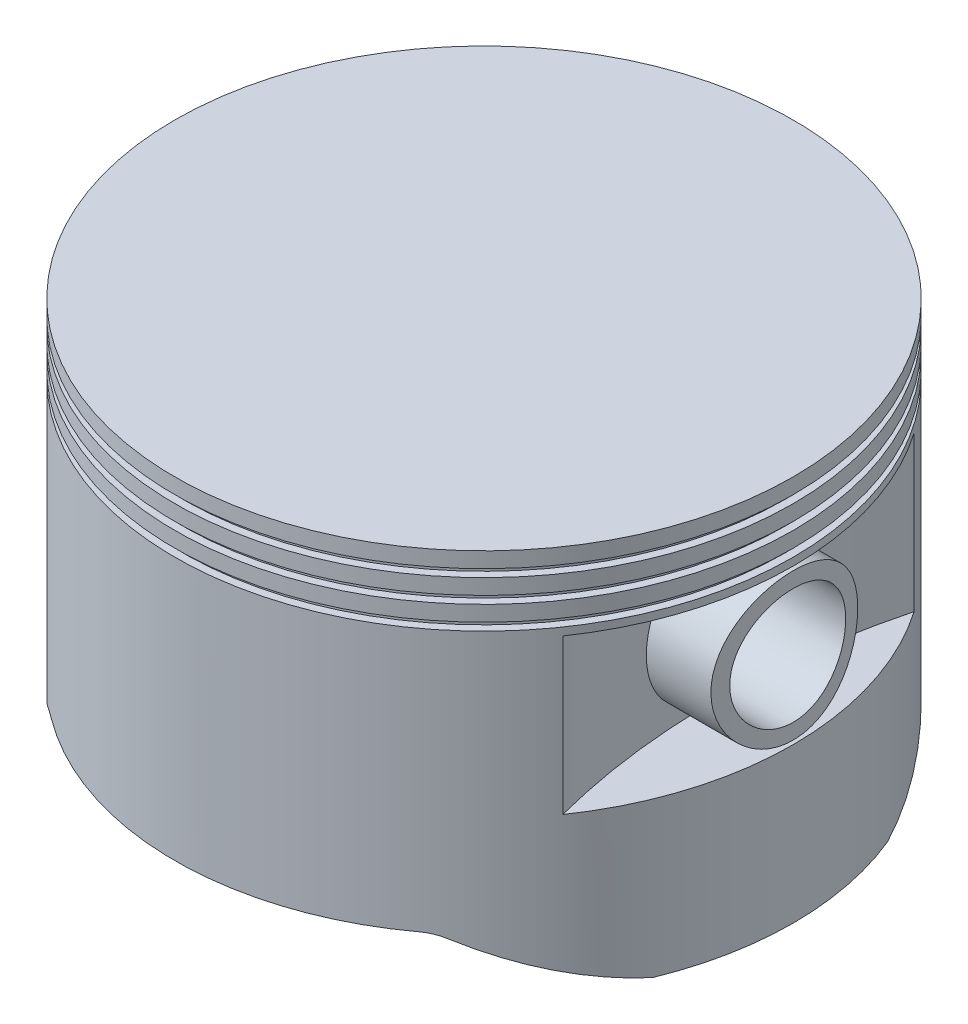
SolidWorks part; units mm, degrees
material "___"
ref_plane "Front Plane" through (0, 0, 0) normal (0, 0, 1) x (1, 0, 0)
ref_plane "Top Plane" through (0, 0, 0) normal (0, 1, 0) x (1, 0, 0)
ref_plane "Right Plane" through (0, 0, 0) normal (1, 0, 0) x (0, 0, -1)
sketch "Sketch1" plane through (0, 0, 0) normal (0, 0, 1) x (1, 0, 0)
  line L1 (0, 25) -> (-40, 25)
  line L2 (0, 25) -> (0, -25)
  line L3 (0, -25) -> (-40, -25)
  line L4 (-40, 25) -> (-40, -25)
  point P4 (-40, 11.1334)
  point P6 (0, 0)
  dimension "D1" = 50
  dimension "D2" = 40
revolve "Revolve1" add sketch "Sketch1" angle 360 about L2
sketch "Sketch2" plane through (0, 0, 0) normal (0, 0, 1) x (1, 0, 0)
  line L0 (-37, -25) -> (-25.8038, -18.5359)
  line L1 (-40, -25) -> (40, -25) construction
  line L2 (-23.8038, -18) -> (23.8038, -18)
  line L3 (0, -18) -> (0, -25) construction
  line L4 (37, -25) -> (-37, -25)
  line L5 (37, -25) -> (25.8038, -18.5359)
  arc A0 (-25.8038, -18.5359) -> (-23.8038, -18) centre (-23.8038, -22) cw
  arc A1 (25.8038, -18.5359) -> (23.8038, -18) centre (23.8038, -22) ccw
  dimension "D3" = 4
  dimension "D1" = 7
  dimension "D2" = 30
  dimension "D4" = 74
extrude "Cut-Extrude1" cut sketch "Sketch2" against normal mid plane 110
ref_plane "Plane1" through (0, -5, 0) normal (0, -1, 0) x (-1, 0, 0)
sketch "Sketch3" plane through (0, -5, 0) normal (0, -1, 0) x (-1, 0, 0)
  circle A0 centre (-120, 0) radius 90
  circle A1 centre (120, 0) radius 90
  circle A3 centre (0, 0) radius 40
  dimension "D3" = 180
  dimension "D5" = 80
  dimension "D1" = 120
  dimension "D2" = 120
extrude "Cut-Extrude4" cut sketch "Sketch3" against normal blind 20
sketch "Sketch4" plane through (0, 0, 0) normal (1, 0, 0) x (0, 0, -1)
  line L0 (-15.1987, -25) -> (15.1987, -25) construction
  circle A0 centre (0, 5) radius 9.5
  dimension "D2" = 19
  dimension "D1" = 30
extrude "Boss-Extrude1" add sketch "Sketch4" along normal up to surface and the other way up to surface up to face at (0, -20.6595, 0) other way up to face at (0, -20.6595, 0)
sketch "Sketch5" plane through (0, 0, 0) normal (1, 0, 0) x (0, 0, -1)
  circle A0 centre (0, 5) radius 7.5
  circle A1 centre (0, 5) radius 9.5 construction
  dimension "D1" = 15
extrude "Cut-Extrude5" cut sketch "Sketch5" against normal mid plane 110
sketch "Sketch6" plane through (0, 0, 0) normal (0, 0, 1) x (1, 0, 0)
  line L0 (-40, 25) -> (-40, 15) construction
  line L1 (-40, 23) -> (-39, 23)
  line L2 (-40, 23) -> (-40, 22)
  line L3 (-40, 22) -> (-39, 22)
  line L4 (-39, 23) -> (-39, 22)
  line L5 (40, 25) -> (-40, 25) construction
  line L6 (-40, 20) -> (-39, 20)
  line L7 (-40, 20) -> (-40, 19)
  line L8 (-40, 19) -> (-39, 19)
  line L9 (-39, 20) -> (-39, 19)
  line L10 (0, 0) -> (0, 25) construction
  line L11 (-40, 17) -> (-39, 17)
  line L12 (-40, 17) -> (-40, 16)
  line L13 (-40, 16) -> (-39, 16)
  line L14 (-39, 17) -> (-39, 16)
  dimension "D1" = 1
  dimension "D2" = 1
  dimension "D3" = 2
  dimension "D4" = 2
  dimension "D5" = 1
  dimension "D6" = 2
revolve "Cut-Revolve1" cut sketch "Sketch6" angle 360 about L10
